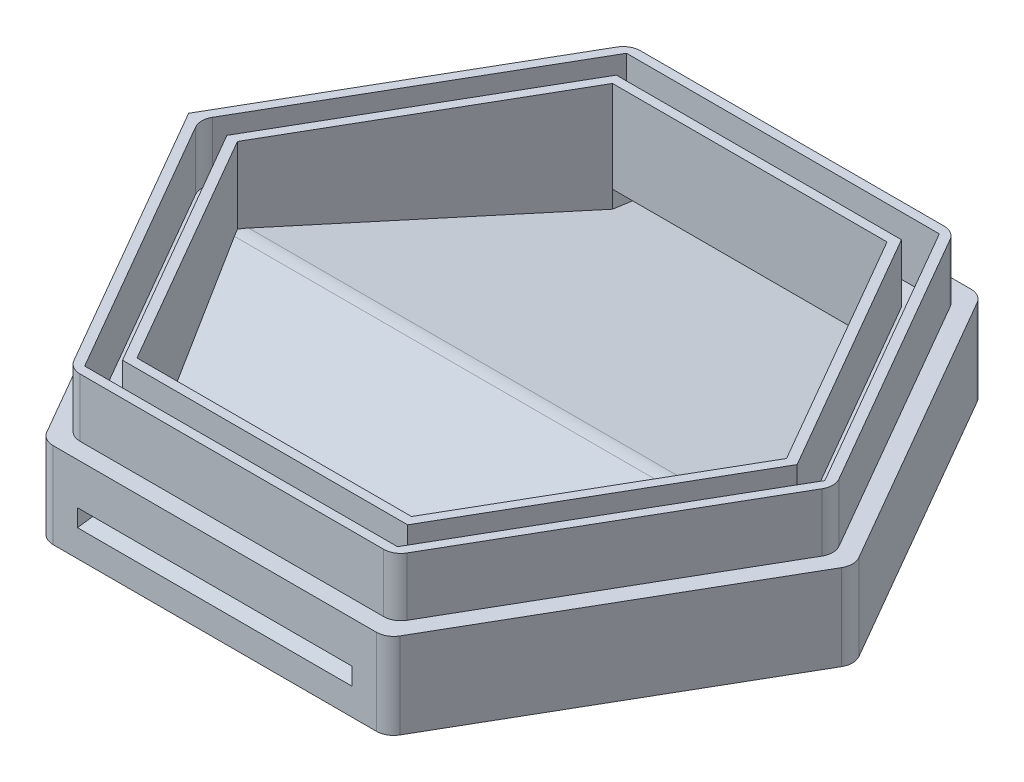
SolidWorks part; units mm, degrees
ref_plane "Front Plane" through (0, 0, 0) normal (0, 0, 1) x (1, 0, 0)
ref_plane "Top Plane" through (0, 0, 0) normal (0, 1, 0) x (1, 0, 0)
ref_plane "Right Plane" through (0, 0, 0) normal (1, 0, 0) x (0, 0, -1)
sketch "Sketch1" plane through (0, 0, 0) normal (0, 1, 0) x (1, 0, 0)
  line L1 (0, 0) -> (-50, 86.6025)
  line L2 (-50, 86.6025) -> (-150, 86.6025)
  line L3 (-150, 86.6025) -> (-200, 0)
  line L4 (-200, 0) -> (-150, -86.6025)
  line L5 (-150, -86.6025) -> (-50, -86.6025)
  line L6 (-50, -86.6025) -> (0, 0)
  dimension "200" = 200
extrude "Boss-Extrude1" add sketch "Sketch1" along normal blind 25
sketch "Sketch6" plane through (0, 25, 0) normal (0, 1, 0) x (1, 0, 0)
  line L0 (-100, -86.6025) -> (-100, 86.6025) construction
  line L3 (0, 0) -> (-200, 0) construction
  line L4 (-150, -86.6025) -> (-50, -86.6025) construction
  line L5 (-50, 86.6025) -> (-150, 86.6025) construction
  line L7 (-180, 0) -> (-140, -69.282)
  line L8 (-140, -69.282) -> (-60, -69.282)
  line L9 (-60, -69.282) -> (-20, 0)
  line L10 (-20, 0) -> (-60, 69.282)
  line L11 (-60, 69.282) -> (-140, 69.282)
  line L12 (-140, 69.282) -> (-180, 0)
  circle A0 centre (-100, 0) radius 69.282 construction
  dimension "D1" = 160
extrude "Cut-Extrude1" cut sketch "Sketch6" against normal blind 5
ref_plane "Plane3" through (0, 36.0941, 6.3644) normal (0, 0.9848, 0.1736) x (1, 0, 0)
sketch "Sketch10" plane through (0, 20, 0) normal (0, 1, 0) x (1, 0, 0)
  line L0 (-100, 69.282) -> (-100, -69.282) construction
  line L1 (-60, 69.282) -> (-140, 69.282) construction
  line L2 (-140, -69.282) -> (-60, -69.282) construction
  line L3 (-180, 0) -> (-20, 0) construction
  line L4 (-60, -69.282) -> (-140, 69.282) construction
  line L5 (-40, 34.641) -> (-160, -34.641) construction
  line L6 (-20, 0) -> (-60, 69.282) construction
  line L7 (-180, 0) -> (-140, -69.282) construction
  line L8 (-140, -69.282) -> (-60, 69.282) construction
  line L9 (-40, -34.641) -> (-160, 34.641) construction
  line L10 (-60, -69.282) -> (-20, 0) construction
  line L11 (-140, 69.282) -> (-180, 0) construction
ref_plane "Plane10" through (-100, 0, 0) normal (1, 0, 0) x (0, 0, -1)
sketch "Sketch21" plane through (-100, 0, 0) normal (1, 0, 0) x (0, 0, -1)
  line L0 (69.282, 20) -> (69.282, 10.263)
  line L2 (69.282, 10.263) -> (0, 20)
  line L3 (0, 25) -> (0, 0) construction
  line L4 (0, 0) -> (0, 20) construction
  line L5 (0, 20) -> (69.282, 20)
  line L6 (69.282, 25) -> (69.282, 20) construction
  line L7 (0, 20) -> (69.282, 20) construction
  dimension "D1" = 8
extrude "Cut-Extrude7" cut sketch "Sketch21" along normal up to surface and the other way up to surface up to face at (-40, 22.5, -34.641) other way up to face at (-160, 22.5, -34.641)
sketch "Sketch22" plane through (-100, 0, 0) normal (1, 0, 0) x (0, 0, -1)
  line L0 (0, 20) -> (-69.282, 10.263)
  line L1 (-69.282, 10.263) -> (-69.282, 20)
  line L2 (-69.282, 20) -> (0, 20)
  line L3 (69.282, 25) -> (69.282, 10.263) construction
  line L4 (69.282, 10.263) -> (69.282, 25) construction
  line L5 (69.282, 10.263) -> (-69.282, 10.263) construction
  dimension "D1" = 8
extrude "Cut-Extrude8" cut sketch "Sketch22" along normal up to surface and the other way up to surface up to face at (-40, 22.5, 34.641) other way up to face at (-160, 22.5, 34.641)
sketch "Sketch23" plane through (-100, 0, 0) normal (1, 0, 0) x (0, 0, -1)
  line L0 (69.282, 10.263) -> (89.282, 7.4522)
  line L1 (89.282, 7.4522) -> (89.282, 12.5014)
  line L2 (89.282, 12.5014) -> (69.282, 15.3122)
  line L3 (69.282, 10.263) -> (69.282, 25) construction
  line L4 (0, 20) -> (69.282, 10.263) construction
  line L5 (69.282, 15.3122) -> (69.282, 10.263)
  line L6 (0, 25) -> (0, 38.3565) construction
  line L7 (-69.282, 15.3122) -> (-69.282, 10.263)
  line L8 (-89.282, 12.5014) -> (-69.282, 15.3122)
  line L9 (-89.282, 7.4522) -> (-89.282, 12.5014)
  line L10 (-69.282, 10.263) -> (-89.282, 7.4522)
  dimension "D1" = 5
  dimension "D2" = 20
extrude "Cut-Extrude9" cut sketch "Sketch23" against normal up to vertex (40 mm away) and the other way up to vertex (40 mm away)
fillet "Fillet2" radius 15 1 edges at (-100, 20, 0)
sketch "Sketch27" plane through (0, 25, 0) normal (0, 1, 0) x (1, 0, 0)
  line L0 (0, 0) -> (-200, 0) construction
  line L1 (-100, 86.6025) -> (-100, -86.6025) construction
  line L2 (-50, 86.6025) -> (-150, 86.6025) construction
  line L3 (-150, -86.6025) -> (-50, -86.6025) construction
  line L4 (-140, 69.282) -> (-180, 0) construction
  line L5 (-10, 0) -> (-55, 77.9423) construction
  line L6 (-55, 77.9423) -> (-145, 77.9423) construction
  line L7 (-145, 77.9423) -> (-190, 0) construction
  line L8 (-190, 0) -> (-145, -77.9423) construction
  line L9 (-145, -77.9423) -> (-55, -77.9423) construction
  line L10 (-55, -77.9423) -> (-10, 0) construction
  line L23 (-15.7735, 0) -> (-57.8868, 72.9423) construction
  line L24 (-57.8868, 72.9423) -> (-142.1132, 72.9423) construction
  line L25 (-142.1132, 72.9423) -> (-184.2265, 0) construction
  line L26 (-184.2265, 0) -> (-142.1132, -72.9423) construction
  line L27 (-142.1132, -72.9423) -> (-57.8868, -72.9423) construction
  line L28 (-57.8868, -72.9423) -> (-15.7735, 0) construction
  line L29 (-150, 86.6025) -> (-200, 0) construction
  line L30 (-178.7947, 2.0876) -> (-140, 69.282) construction
  line L32 (-16.9282, 0) -> (-58.4641, 71.9423)
  line L33 (-58.4641, 71.9423) -> (-141.5359, 71.9423)
  line L34 (-141.5359, 71.9423) -> (-183.0718, 0)
  line L35 (-183.0718, 0) -> (-141.5359, -71.9423)
  line L36 (-141.5359, -71.9423) -> (-58.4641, -71.9423)
  line L37 (-58.4641, -71.9423) -> (-16.9282, 0)
  line L38 (-5.7735, 0) -> (-52.8868, 81.6025)
  line L39 (-21.2053, 2.0876) -> (-60, 69.282) construction
  line L40 (-50, -86.6025) -> (0, 0) construction
  line L41 (-20, 0) -> (-60, 69.282)
  line L42 (-60, 69.282) -> (-140, 69.282)
  line L43 (-140, 69.282) -> (-180, 0)
  line L44 (-180, 0) -> (-140, -69.282)
  line L45 (-140, -69.282) -> (-60, -69.282)
  line L46 (-60, -69.282) -> (-20, 0)
  line L47 (-8.8453, 0) -> (-54.4226, 78.9423)
  line L48 (-54.4226, 78.9423) -> (-145.5774, 78.9423)
  line L49 (-145.5774, 78.9423) -> (-191.1547, 0)
  line L50 (-191.1547, 0) -> (-145.5774, -78.9423)
  line L51 (-145.5774, -78.9423) -> (-54.4226, -78.9423)
  line L52 (-54.4226, -78.9423) -> (-8.8453, 0)
  line L53 (-52.8868, 81.6025) -> (-147.1132, 81.6025)
  line L54 (-147.1132, 81.6025) -> (-194.2265, 0)
  line L55 (-194.2265, 0) -> (-147.1132, -81.6025)
  line L56 (-147.1132, -81.6025) -> (-52.8868, -81.6025)
  line L57 (-52.8868, -81.6025) -> (-5.7735, 0)
  circle A0 centre (-100, 0) radius 77.9423 construction
  circle A1 centre (-100, 0) radius 72.9423 construction
  circle A2 centre (-100, 0) radius 71.9423 construction
  circle A3 centre (-100, 0) radius 69.282 construction
  circle A4 centre (-100, 0) radius 78.9423 construction
  circle A5 centre (-100, 0) radius 81.6025 construction
  line M20 (-180, 0) -> (-140, 69.282)
  line M21 (-140, 69.282) -> (-60, 69.282)
  line M22 (-60, 69.282) -> (-20, 0)
  line M23 (-20, 0) -> (-60, -69.282)
  line M24 (-60, -69.282) -> (-140, -69.282)
  line M25 (-140, -69.282) -> (-180, 0)
  dimension "D1" = 180
  dimension "D2" = 5
  dimension "D3" = 1
  dimension "D4" = 2.6603
  dimension "1" = 1
extrude "Boss-Extrude5" add sketch "Sketch27" along normal blind 17 contours L56 L57 L38 L53 L54 L55 L52 L51 L50 L49 L48 L47 | L36 L37 L32 L33 L34 L35 M25 M20 M21 M22 M23 M24
fillet "Fillet3" radius 5 12 edges at (-50, 12.5, -86.6025) (0, 12.5, 0) (-50, 12.5, 86.6025) (-150, 12.5, 86.6025) (-200, 12.5, 0) (-150, 12.5, -86.6025) (-52.8868, 33.5, -81.6025) (-147.1132, 33.5, -81.6025) (-191.1547, 33.5, 0) (-147.1132, 33.5, 81.6025) (-5.7735, 33.5, 0) (-52.8868, 33.5, 81.6025)
